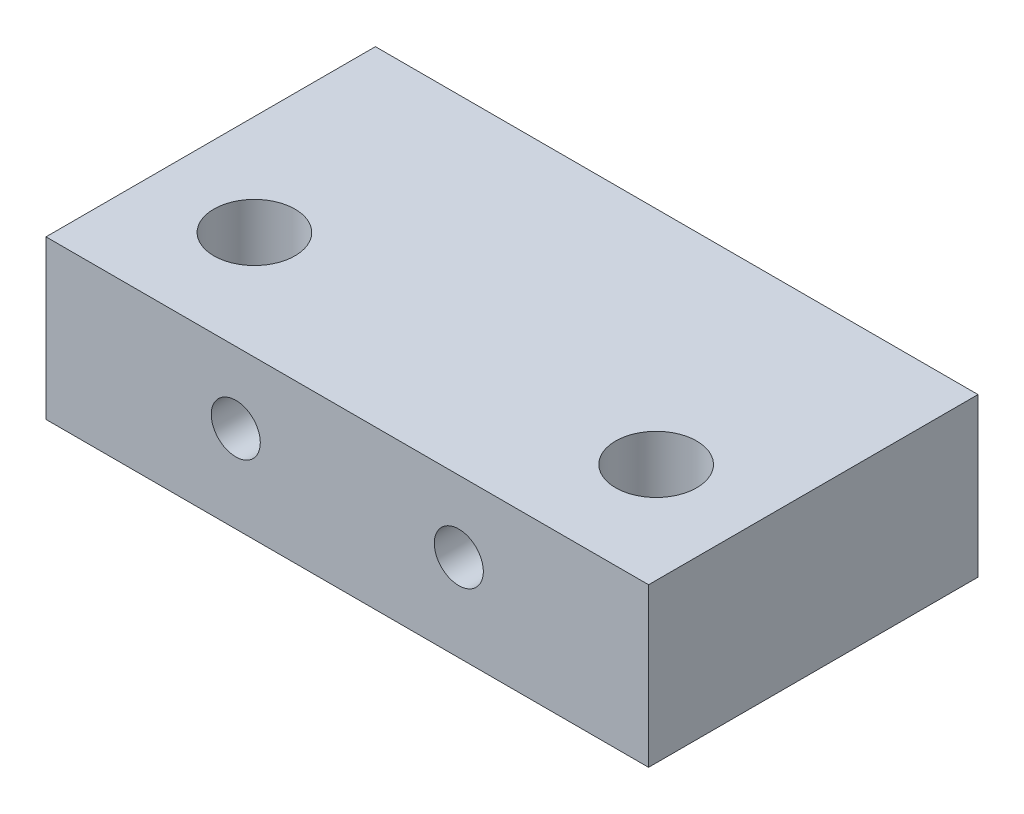
SolidWorks part; units mm, degrees
ref_plane "Front Plane" through (0, 0, 0) normal (0, 0, 1) x (1, 0, 0)
ref_plane "Top Plane" through (0, 0, 0) normal (0, 1, 0) x (1, 0, 0)
ref_plane "Right Plane" through (0, 0, 0) normal (1, 0, 0) x (0, 0, -1)
sketch "Sketch1" plane through (0, 0, 0) normal (0, 1, 0) x (1, 0, 0)
  line L0 (-19.05, 20.828) -> (-19.05, 0) construction
  line L1 (-38.1, 20.828) -> (0, 20.828)
  line L2 (-38.1, 20.828) -> (-38.1, 0)
  line L3 (-38.1, 0) -> (0, 0)
  line L4 (0, 20.828) -> (0, 0)
  circle A0 centre (-31.75, 6.828) radius 2.564
  circle A2 centre (-6.35, 6.828) radius 2.564
  point P9 (-19.05, 0)
  point P10 (0, 0)
  dimension "D3" = 5.128
  dimension "D1" = 38.1
  dimension "D2" = 20.828
  dimension "D4" = 6.828
  dimension "D5" = 6.35
extrude "Boss-Extrude1" add sketch "Sketch1" along normal blind 10
sketch "Sketch2" plane through (0, 0, 0) normal (0, 0, 1) x (1, 0, 0)
  line L0 (-38.1, 10) -> (-38.1, 0) construction
  line L1 (-19.05, 10) -> (-19.05, 0) construction
  line L2 (-38.1, 10) -> (0, 10) construction
  line L3 (-38.1, 0) -> (0, 0) construction
  line L4 (-26.1, 5.5) -> (-19.05, 5.5) construction
  circle A0 centre (-26.1, 5.5) radius 1.55
  circle A2 centre (-12, 5.5) radius 1.55
  point P13 (0, 0)
  dimension "D1" = 3.1
  dimension "D2" = 5.5
  dimension "D4" = 12
extrude "Cut-Extrude1" cut sketch "Sketch2" against normal blind 10
